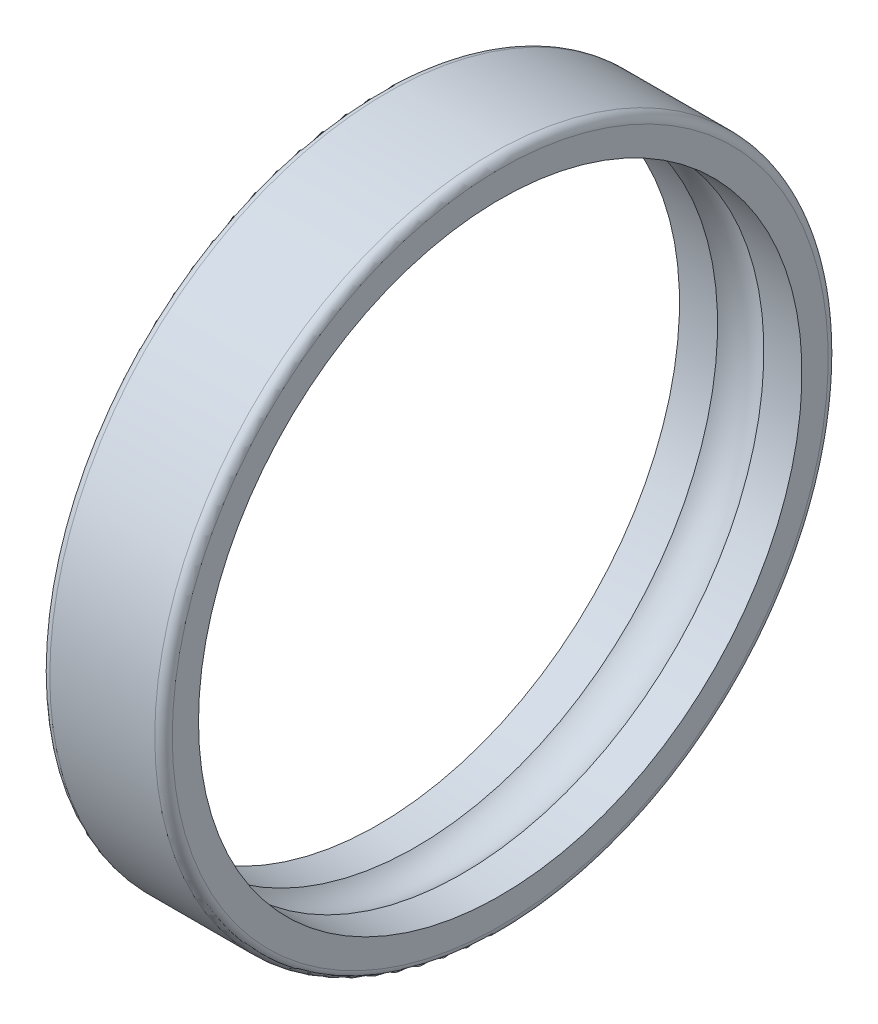
SolidWorks part; units mm, degrees
ref_plane "Plan1" through (0, 0, 0) normal (0, 0, 1) x (1, 0, 0)
ref_plane "Plan2" through (0, 0, 0) normal (0, 1, 0) x (1, 0, 0)
ref_plane "Plan3" through (0, 0, 0) normal (1, 0, 0) x (0, 0, -1)
sketch "Esquisse1" plane through (0, 0, 0) normal (0, 0, 1) x (1, 0, 0)
  line L0 (-5, 17.5) -> (-5, 27.5) construction
  line L1 (-4.2857, 27.5) -> (4.2857, 27.5)
  line L2 (-5, 26.7857) -> (-5, 24.6429)
  line L3 (-5, 24.6429) -> (-1.8898, 24.6429)
  line L4 (5, 26.7857) -> (5, 24.6429)
  line L5 (5, 17.5) -> (5, 27.5) construction
  line L6 (-5, 27.5) -> (5, 27.5) construction
  line L7 (1.8898, 24.6429) -> (5, 24.6429)
  line L8 (0, 0) -> (15, 0) construction
  line L9 (0, 0) -> (54, 0) construction
  arc A0 (4.2857, 27.5) -> (5, 26.7857) centre (4.2857, 26.7857) cw
  arc A1 (-4.2857, 27.5) -> (-5, 26.7857) centre (-4.2857, 26.7857) ccw
  arc A2 (1.8898, 24.6429) -> (-1.8898, 24.6429) centre (0, 22.5) ccw
  point P12 (5, 27.5)
  dimension "D2" = 0.7143
  dimension "D3" = 2.8571
  dimension "D1" = 2.8571
revolve "Base-Révolution" add sketch "Esquisse1" angle 360 about L8
